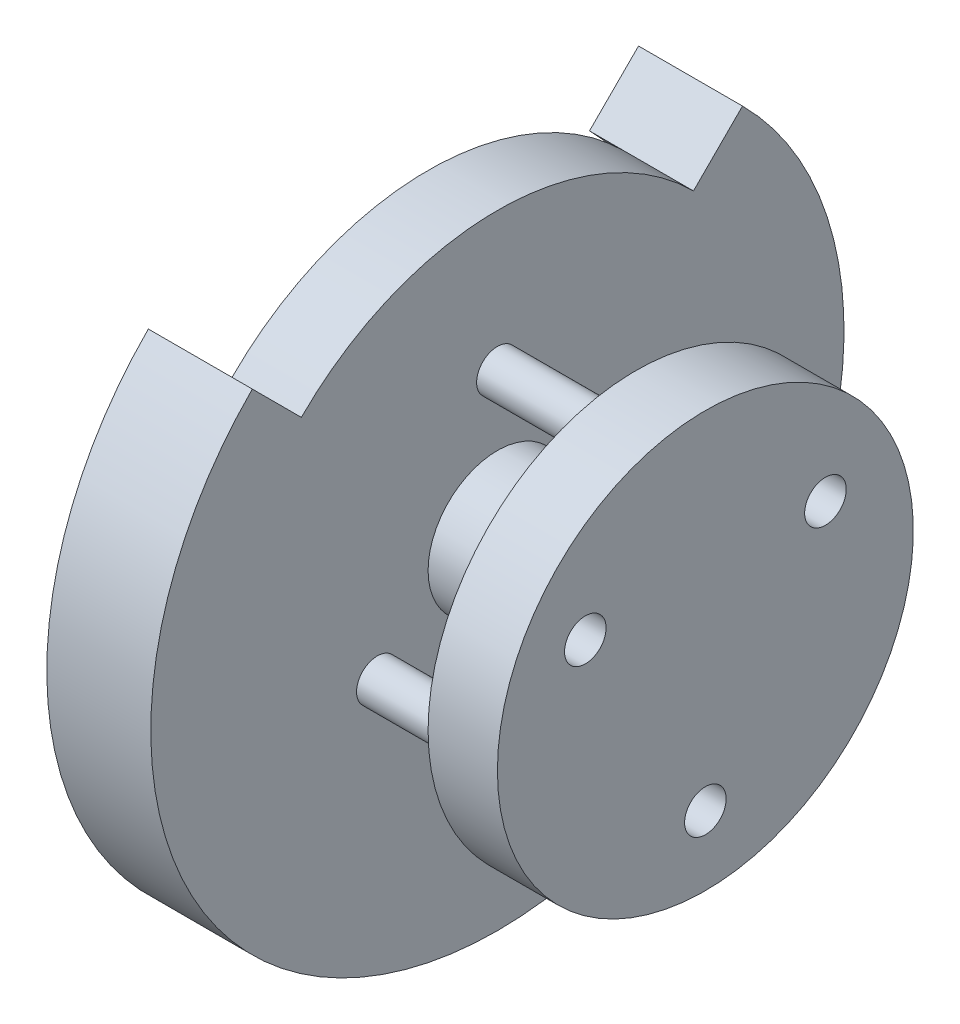
SolidWorks part; units mm, degrees
ref_plane "Alzado" through (0, 0, 0) normal (0, 0, 1) x (1, 0, 0)
ref_plane "Planta" through (0, 0, 0) normal (0, 1, 0) x (1, 0, 0)
ref_plane "Vista lateral" through (0, 0, 0) normal (1, 0, 0) x (0, 0, -1)
sketch "Croquis1" plane through (0, 0, 0) normal (0, 1, 0) x (1, 0, 0)
  line L0 (0, 0) -> (22.5, 0)
  line L1 (22.5, 0) -> (22.5, 15)
  line L2 (22.5, 15) -> (17.5, 15)
  line L3 (17.5, 15) -> (17.5, 5)
  line L4 (17.5, 5) -> (7.5, 5)
  line L5 (7.5, 5) -> (7.5, 25)
  line L6 (7.5, 25) -> (0, 25)
  line L7 (0, 25) -> (0, 20)
  line L8 (0, 20) -> (2.5, 20)
  line L9 (2.5, 20) -> (2.5, 10)
  line L10 (2.5, 10) -> (0, 10)
  line L11 (0, 10) -> (0, 0)
  dimension "D1" = 10
  dimension "D2" = 5
  dimension "D3" = 7.5
  dimension "D4" = 2.5
  dimension "D5" = 10
  dimension "D6" = 10
  dimension "D7" = 5
  dimension "D8" = 20
  dimension "D9" = 15
revolve "Revolución1" add sketch "Croquis1" angle 360 about L0
sketch "Croquis2" plane through (0, 0, 0) normal (-1, 0, 0) x (0, 0, 1)
  line L0 (0, 0) -> (17.6777, 17.6777)
  line L1 (-25, 0) -> (25, 0)
  line L2 (0, 0) -> (-17.6777, 17.6777)
  circle A0 centre (0, 0) radius 25 construction
  circle A1 centre (0, 0) radius 20
  circle A2 centre (0, 0) radius 25
  dimension "D1" = 25
  dimension "D2" = 45
  dimension "D3" = 45
extrude "Cortar-Extruir2" cut sketch "Croquis2" against normal blind 7.5 contours L0 A2 L2 A1
sketch "Croquis4" plane through (0, 0, 0) normal (-1, 0, 0) x (0, 0, 1)
  line L0 (-25, 0) -> (25, 0)
  line L1 (0, 0) -> (-2.1789, -24.9049)
  line L2 (0, 0) -> (2.1789, -24.9049)
  arc A0 (-17.6777, 17.6777) -> (17.6777, 17.6777) centre (0, 0) ccw construction
  circle A1 centre (0, 0) radius 20
  circle A2 centre (0, 0) radius 25
  arc M1 (-17.6777, 17.6777) -> (17.6777, 17.6777) centre (0, 0) ccw
  arc M3 (14.1421, 14.1421) -> (-14.1421, 14.1421) centre (0, 0) cw
  dimension "D1" = 85
  dimension "D2" = 85
extrude "Cortar-Extruir3" cut sketch "Croquis4" against normal blind 2.5 contours L2 L1 M3 M1
sketch "Croquis5" plane through (22.5, 0, 0) normal (1, 0, 0) x (0, 0, -1)
  circle A0 centre (0, 0) radius 10
  circle A1 centre (0, -10) radius 1.5
  circle A2 centre (-8.6603, 5) radius 1.5
  circle A3 centre (8.6603, 5) radius 1.5
  point P12 (0, 0)
  dimension "D1" = 3
  dimension "D2" = 20
  dimension "D3" = 3
extrude "Cortar-Extruir4" cut sketch "Croquis5" against normal blind 5 contours A0 A2 | A0 A2 | A0 A3 | A0 A3 | A0 A1 | A0 A1
sketch "Croquis6" plane through (22.5, 0, 0) normal (1, 0, 0) x (0, 0, -1)
  circle A0 centre (0, 0) radius 10
  circle A1 centre (0, 10) radius 1.5
  circle A2 centre (8.6603, -5) radius 1.5
  circle A3 centre (-8.6603, -5) radius 1.5
  point P12 (0, 0)
  dimension "D1" = 3
  dimension "D2" = 20
extrude "Saliente-Extruir1" add sketch "Croquis6" against normal blind 15 contours A0 A2 | A0 A2 | A0 A3 | A0 A3 | A1
sketch "Croquis7" plane through (0, 0, 0) normal (-1, 0, 0) x (0, 0, 1)
  line L0 (-0.7966, 3.0579) -> (-0.2353, 1.8854)
  line L1 (0, 0) -> (0, 3.74)
  line L2 (0, 5) -> (0, 5.4134)
  line L3 (0.7966, 3.0579) -> (0.2353, 1.8854)
  line L4 (1.599, 2.7256) -> (1.1668, 1.4995)
  line L5 (2.7256, 1.599) -> (1.4995, 1.1668)
  line L6 (3.0579, 0.7966) -> (1.8854, 0.2353)
  line L7 (3.0579, -0.7966) -> (1.8854, -0.2353)
  line L8 (2.7256, -1.599) -> (1.4995, -1.1668)
  line L9 (1.599, -2.7256) -> (1.1668, -1.4995)
  line L10 (0.7966, -3.0579) -> (0.2353, -1.8854)
  line L11 (-0.7966, -3.0579) -> (-0.2353, -1.8854)
  line L12 (-1.599, -2.7256) -> (-1.1668, -1.4995)
  line L13 (-2.7256, -1.599) -> (-1.4995, -1.1668)
  line L14 (-3.0579, -0.7966) -> (-1.8854, -0.2353)
  line L15 (-3.0579, 0.7966) -> (-1.8854, 0.2353)
  line L16 (-2.7256, 1.599) -> (-1.4995, 1.1668)
  line L17 (-1.599, 2.7256) -> (-1.1668, 1.4995)
  circle A0 centre (0, 0) radius 1.9
  circle A1 centre (0, 0) radius 3.16
  circle A2 centre (0, 0) radius 3.74
  circle A3 centre (0, 0) radius 5
  arc A4 (-0.7966, 3.0579) -> (-1.21, 3.5389) centre (-2.1873, 2.2806) ccw
  arc A5 (1.599, 2.7256) -> (1.6467, 3.3579) centre (0.066, 3.1593) ccw
  arc A6 (3.3579, 1.6467) -> (2.7256, 1.599) centre (3.1593, 0.066) ccw
  arc A7 (1.21, 3.5389) -> (0.7966, 3.0579) centre (2.1873, 2.2806) ccw
  arc A8 (3.0579, 0.7966) -> (3.5389, 1.21) centre (2.2806, 2.1873) ccw
  arc A9 (3.5389, -1.21) -> (3.0579, -0.7966) centre (2.2806, -2.1873) ccw
  arc A10 (2.7256, -1.599) -> (3.3579, -1.6467) centre (3.1593, -0.066) ccw
  arc A11 (1.6467, -3.3579) -> (1.599, -2.7256) centre (0.066, -3.1593) ccw
  arc A12 (0.7966, -3.0579) -> (1.21, -3.5389) centre (2.1873, -2.2806) ccw
  arc A13 (-1.21, -3.5389) -> (-0.7966, -3.0579) centre (-2.1873, -2.2806) ccw
  arc A14 (-1.599, -2.7256) -> (-1.6467, -3.3579) centre (-0.066, -3.1593) ccw
  arc A15 (-3.3579, -1.6467) -> (-2.7256, -1.599) centre (-3.1593, -0.066) ccw
  arc A16 (-3.0579, -0.7966) -> (-3.5389, -1.21) centre (-2.2806, -2.1873) ccw
  arc A17 (-3.5389, 1.21) -> (-3.0579, 0.7966) centre (-2.2806, 2.1873) ccw
  arc A18 (-2.7256, 1.599) -> (-3.3579, 1.6467) centre (-3.1593, 0.066) ccw
  arc A19 (-1.6467, 3.3579) -> (-1.599, 2.7256) centre (-0.066, 3.1593) ccw
  point P75 (0, 0)
  dimension "D1" = 3.8
  dimension "D2" = 6.32
  dimension "D3" = 7.48
  dimension "D4" = 10
  dimension "D5" = 2.42
  dimension "D6" = 1.3
  dimension "D7" = 1.3
  dimension "D8" = 8
extrude "Cortar-Extruir5" cut sketch "Croquis7" against normal blind 5
